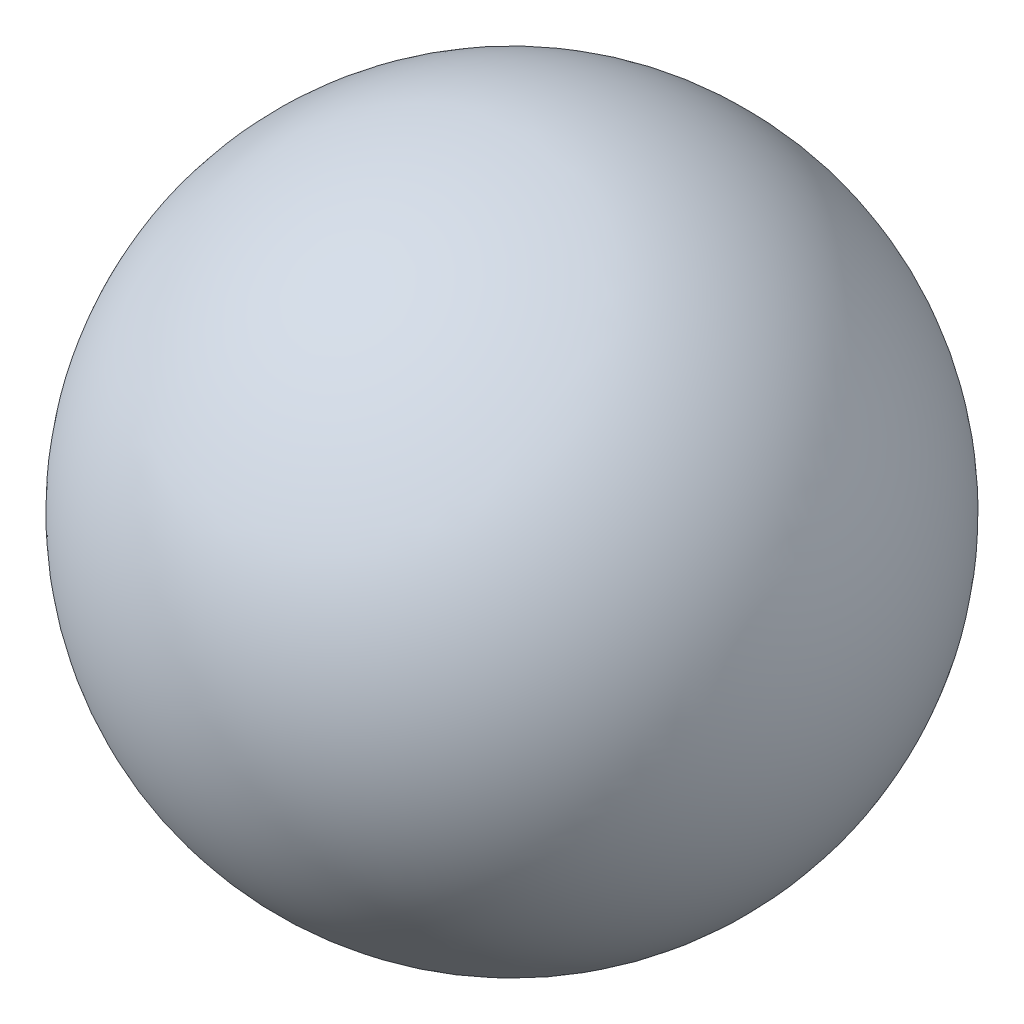
SolidWorks part; units mm, degrees
ref_plane "Front Plane" through (0, 0, 0) normal (0, 0, 1) x (1, 0, 0)
ref_plane "Top Plane" through (0, 0, 0) normal (0, 1, 0) x (1, 0, 0)
ref_plane "Right Plane" through (0, 0, 0) normal (1, 0, 0) x (0, 0, -1)
sketch "Sketch1" plane through (0, 0, 0) normal (0, 0, 1) x (1, 0, 0)
  line L0 (-139.7, 0) -> (139.7, 0)
  arc A0 (-139.7, 0) -> (139.7, 0) centre (0, 0) ccw
  dimension "D1" = 279.4
revolve "Revolve1" add sketch "Sketch1" angle 360 about L0
